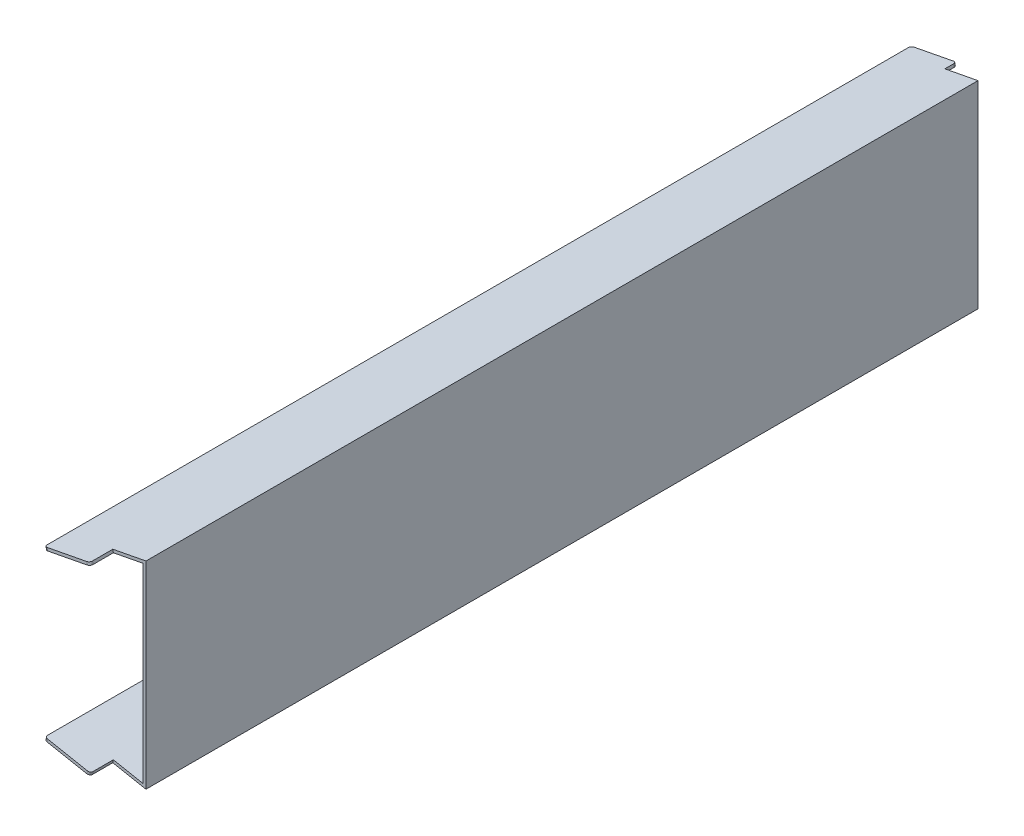
SolidWorks part; units mm, degrees
ref_plane "Front Plane" through (0, 0, 0) normal (0, 0, 1) x (1, 0, 0)
ref_plane "Top Plane" through (0, 0, 0) normal (0, 1, 0) x (1, 0, 0)
ref_plane "Right Plane" through (0, 0, 0) normal (1, 0, 0) x (0, 0, -1)
sketch "Sketch1" plane through (0, 0, 0) normal (0, 0, 1) x (1, 0, 0)
  line L0 (-13, 2.5) -> (0, 0)
  line L1 (0, 0) -> (0, 33)
  line L2 (0, 33) -> (-13, 30.5)
  line L3 (-13.0944, 2.009) -> (0.5, -0.6053)
  line L4 (0.5, -0.6053) -> (0.5, 33.6053)
  line L5 (0.5, 33.6053) -> (-13.0944, 30.991)
  line L6 (-13.0944, 30.991) -> (-13, 30.5)
  line L7 (-13, 2.5) -> (-13.0944, 2.009)
  dimension "D1" = 33
  dimension "D2" = 28
  dimension "D3" = 13
  dimension "D4" = 0.5
extrude "Boss-Extrude1" add sketch "Sketch1" along normal blind 144
sketch "Sketch2" plane through (-6.2143, 32.3141, 0) normal (-0.1888, 0.982, 0) x (0.982, 0.1888, 0)
  line L0 (-7.0062, 0) -> (-7.0062, 1.5)
  line L1 (-6.5062, 2) -> (0.4938, 2)
  line L2 (0.9938, 1.5) -> (0.9938, 0)
  line L3 (6.8373, 0) -> (-7.0062, 0) construction
  line L4 (0.9938, 0) -> (-7.0062, 0)
  line L5 (-7.0062, -144) -> (-7.0062, -147.5)
  line L6 (-6.5062, -148) -> (0.4938, -148)
  line L7 (0.9938, -147.5) -> (0.9938, -144)
  line L8 (6.8373, -144) -> (-7.0062, -144) construction
  line L9 (0.9938, -144) -> (-7.0062, -144)
  arc A0 (0.4938, 2) -> (0.9938, 1.5) centre (0.4938, 1.5) cw
  arc A1 (-7.0062, 1.5) -> (-6.5062, 2) centre (-6.5062, 1.5) cw
  arc A2 (0.4938, -148) -> (0.9938, -147.5) centre (0.4938, -147.5) ccw
  arc A3 (-7.0062, -147.5) -> (-6.5062, -148) centre (-6.5062, -147.5) ccw
  point P16 (0.9938, 2)
  point P19 (-7.0062, 2)
  point P22 (0.9938, -148)
  point P25 (-7.0062, -148)
  dimension "D5" = 0.5
  dimension "D1" = 2
  dimension "D2" = 8
  dimension "D3" = 4
  dimension "D4" = 8
extrude "Boss-Extrude2" add sketch "Sketch2" against normal blind 0.5
sketch "Sketch3" plane through (-0.0944, -0.491, 0) normal (-0.1888, -0.982, 0) x (0.982, -0.1888, 0)
  line L0 (-13.2382, 144) -> (-13.2382, 147.5)
  line L1 (-18.0616, 148) -> (-11.5609, 148) construction
  line L2 (-12.7382, 148) -> (-5.7382, 148)
  line L3 (-5.2382, 147.5) -> (-5.2382, 144)
  line L4 (-13.2382, 0) -> (0.6053, 0)
  line L5 (0.6053, 0) -> (0.6053, 144)
  line L6 (0.6053, 144) -> (-13.2382, 144)
  line L7 (-13.2382, 144) -> (-13.2382, 0)
  line L8 (-13.2382, 0) -> (0.6053, 0)
  line L9 (0.6053, 0) -> (0.6053, 144)
  line L10 (0.6053, 144) -> (-13.2382, 144)
  line L11 (-13.2382, 144) -> (-13.2382, 0)
  line L12 (-13.2382, 0) -> (-13.2382, -1.5)
  line L13 (-11.5609, -2) -> (-18.0616, -2) construction
  line L14 (-12.7382, -2) -> (-5.7382, -2)
  line L15 (-5.2382, -1.5) -> (-5.2382, 0)
  line L16 (-5.2382, 0) -> (-13.2382, 0)
  line L17 (-5.2382, 144) -> (-13.2382, 144)
  arc A0 (-5.7382, 148) -> (-5.2382, 147.5) centre (-5.7382, 147.5) cw
  arc A1 (-13.2382, 147.5) -> (-12.7382, 148) centre (-12.7382, 147.5) cw
  arc A2 (-5.7382, -2) -> (-5.2382, -1.5) centre (-5.7382, -1.5) ccw
  arc A3 (-13.2382, -1.5) -> (-12.7382, -2) centre (-12.7382, -1.5) ccw
  point P12 (-5.2382, 148)
  point P15 (-13.2382, 148)
  point P23 (-5.2382, -2)
  point P26 (-13.2382, -2)
  line M5 (-13.2382, 0) -> (0.6053, 0)
  line M7 (0.6053, 144) -> (-13.2382, 144)
  dimension "D3" = 0.5
  dimension "D5" = 0.5
  dimension "D2" = 8
  dimension "D4" = 8
  dimension "D1" = 0
extrude "Boss-Extrude3" add sketch "Sketch3" against normal blind 0.5 contours A1 L0 L3 A0 L2 M7 | L12 A3 L14 A2 L15 M5
